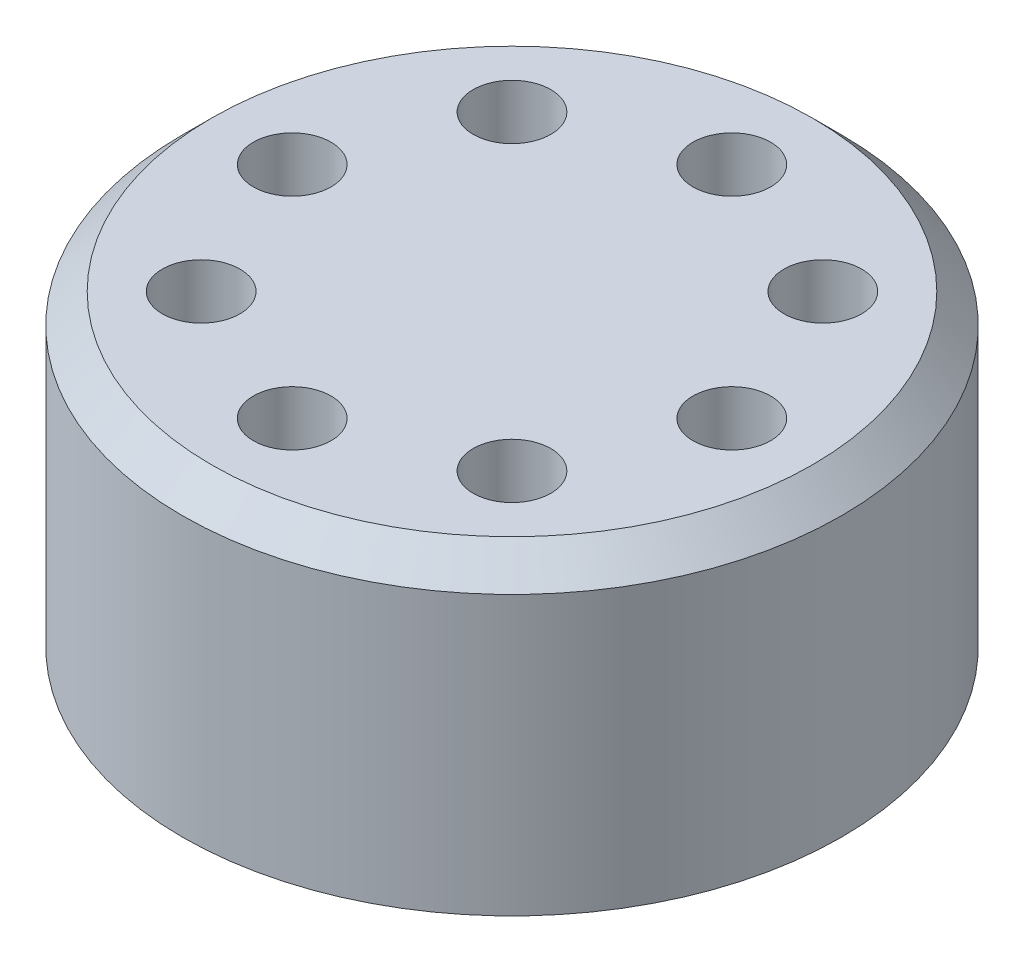
SolidWorks part; units mm, degrees
ref_plane "Front Plane" through (0, 0, 0) normal (0, 0, 1) x (1, 0, 0)
ref_plane "Top Plane" through (0, 0, 0) normal (0, 1, 0) x (1, 0, 0)
ref_plane "Right Plane" through (0, 0, 0) normal (1, 0, 0) x (0, 0, -1)
sketch "Sketch1" plane through (0, 0, 0) normal (0, 1, 0) x (1, 0, 0)
  circle A0 centre (0, 0) radius 22.5
  dimension "D1" = 45
extrude "Boss-Extrude1" add sketch "Sketch1" along normal blind 21
chamfer "Chamfer1" distance 2 angle 45 1 edges at (0, 21, 22.5)
hole_wizard "M5 Clearance Hole1" positions "Sketch2" profile "Sketch3" hole size "M5" standard "ANSI Metric" end condition through all
sketch "Sketch2" plane through (0, 21, 0) normal (0, 1, 0) x (1, 0, 0)
  line L0 (0, 0) -> (15, 0) construction
  line L2 (0, 0) -> (10.6066, 10.6066) construction
  circle A0 centre (0, 0) radius 15 construction
  point P5 (0, 15)
  point P7 (15, 0)
  point P9 (0, -15)
  point P11 (-15, 0)
  point P20 (10.6066, 10.6066)
  point P30 (10.6066, -10.6066)
  point P31 (-10.6066, -10.6066)
  point P32 (-10.6066, 10.6066)
  point P34 (-11.3136, 11.3138)
  point P35 (0, 0)
  dimension "D1" = 30
  dimension "D2" = 45
  dimension "D3" = 4
sketch "Sketch3" plane through (-10.6066, 21, -10.6066) normal (1, 0, 0) x (0, 0, 1)
  line L0 (0, 0) -> (0, 21)
  line L1 (0, 21) -> (2.65, 21)
  line L2 (2.65, 21) -> (2.65, 0)
  line L5 (2.65, 0) -> (0, 0)
  line L11 (0, -6.35) -> (0, 107.95) construction
  dimension "Thru Hole Dia." = 5.3
  dimension "Thru Hole Depth" = 21
